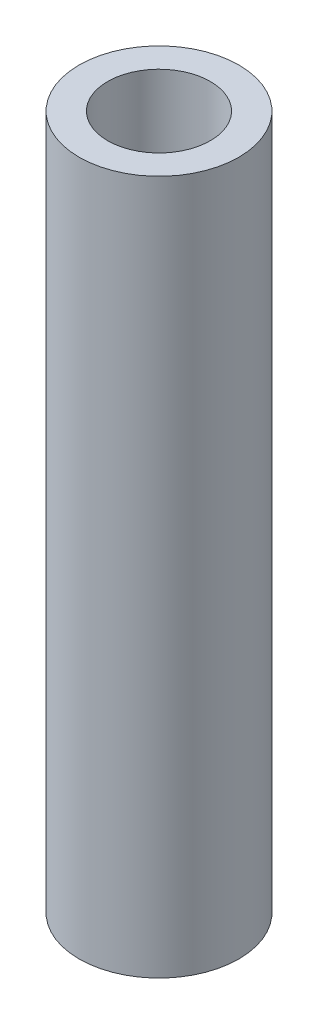
SolidWorks part; units mm, degrees
ref_plane "Front Plane" through (0, 0, 0) normal (0, 0, 1) x (1, 0, 0)
ref_plane "Top Plane" through (0, 0, 0) normal (0, 1, 0) x (1, 0, 0)
ref_plane "Right Plane" through (0, 0, 0) normal (1, 0, 0) x (0, 0, -1)
sketch "Sketch1" plane through (0, 0, 0) normal (0, 1, 0) x (1, 0, 0)
  circle A0 centre (0, 0) radius 3.873
  circle A1 centre (0, 0) radius 2.4892
  dimension "D1" = 7.746
  dimension "D2" = 4.9784
extrude "Boss-Extrude1" add sketch "Sketch1" along normal blind 33.67
